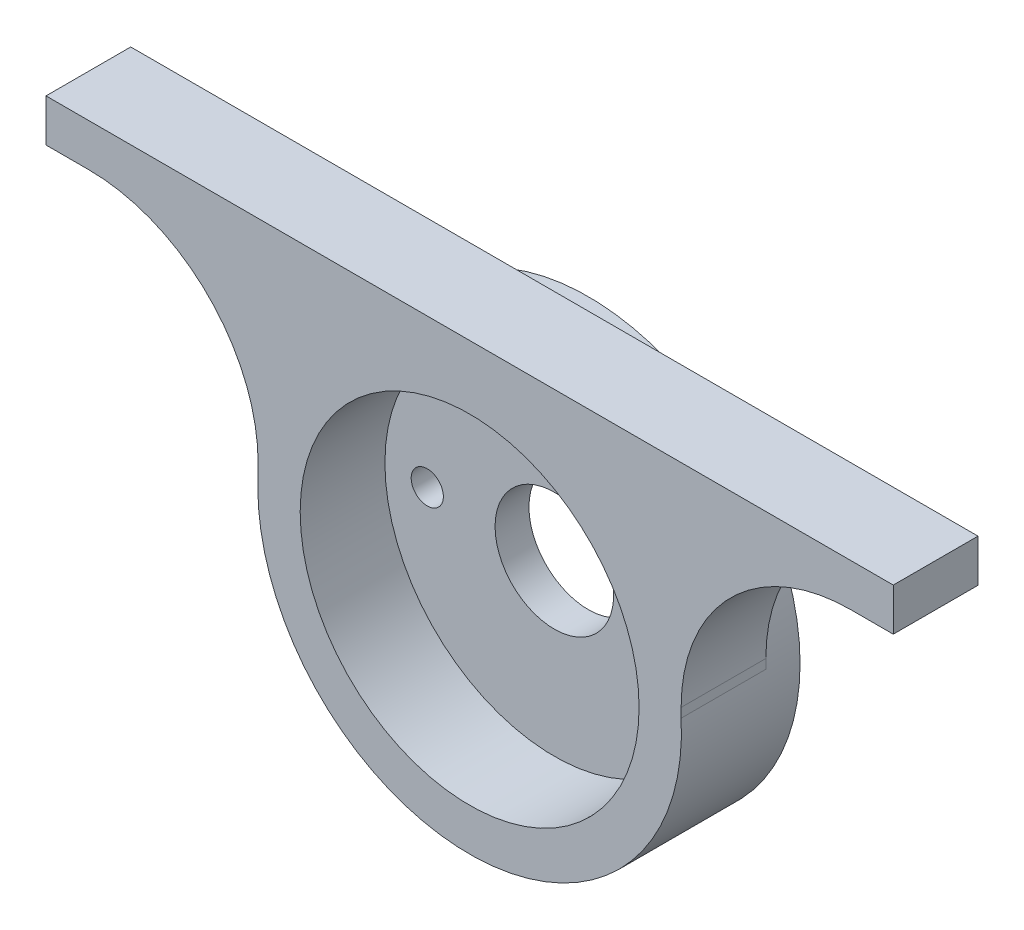
SolidWorks part; units mm, degrees
ref_plane "Front" through (0, 0, 0) normal (0, 0, 1) x (1, 0, 0)
ref_plane "Top" through (0, 0, 0) normal (0, 1, 0) x (1, 0, 0)
ref_plane "Right" through (0, 0, 0) normal (1, 0, 0) x (0, 0, -1)
sketch "Sketch1" plane through (0, 0, 0) normal (0, 0, 1) x (1, 0, 0)
  line L2 (-25, 11.2434) -> (-25, 13.7566)
  line L3 (-25, 13.7566) -> (25, 13.7566)
  line L4 (25, 11.2434) -> (25, 13.7566)
  line L5 (0, 12.5) -> (-25, 12.5) construction
  line L6 (0, 12.5) -> (25, 12.5) construction
  line L7 (25, 11.2434) -> (22.4809, 11.2434)
  line L8 (12.4809, 1.2434) -> (12.4809, 0.6908)
  line L9 (-12.4809, 0.6908) -> (-12.4809, 1.2434)
  line L10 (-22.4809, 11.2434) -> (-25, 11.2434)
  circle A0 centre (0, 0) radius 10
  arc A1 (-12.4809, 0.6908) -> (12.4809, 0.6908) centre (0, 0) ccw
  arc A4 (22.4809, 11.2434) -> (12.4809, 1.2434) centre (22.4809, 1.2434) ccw
  arc A5 (-12.4809, 1.2434) -> (-22.4809, 11.2434) centre (-22.4809, 1.2434) ccw
  point P4 (0, 12.5)
  point P12 (5.4623, 11.2434)
  dimension "D1" = 20
  dimension "D2" = 25
  dimension "D4" = 10
  dimension "D3" = 50
extrude "Boss-Extrude1" add sketch "Sketch1" along normal blind 5 contours L3 L4 A1 L2
sketch "Sketch3" plane through (0, 0, 0) normal (0, 0, -1) x (-1, 0, 0)
  line L0 (-7.5, 0) -> (7.5, 0) construction
  circle A0 centre (0, 0) radius 3.5
  circle A1 centre (0, 0) radius 12.5
  circle A2 centre (7.5, 0) radius 0.95
  circle A3 centre (-7.5, 0) radius 0.95
  dimension "D1" = 7
  dimension "D2" = 25
  dimension "D3" = 1.9
  dimension "D4" = 1.9
  dimension "D5" = 7.5
  dimension "D6" = 7.5
extrude "Boss-Extrude3" add sketch "Sketch3" along normal blind 2
sketch "Sketch4" plane through (0, 13.7566, 0) normal (0, 1, 0) x (1, 0, 0)
  line L0 (25, -5) -> (25, 0) construction
  line L1 (25, 0) -> (-25, 0) construction
  line L2 (-25, -5) -> (-25, 0) construction
  line L3 (25, -5) -> (-25, -5) construction
  circle A0 centre (-20, -5) radius 3
  circle A1 centre (20, -5) radius 3
  circle A2 centre (20, 0) radius 3
  circle A3 centre (-20, 0) radius 3
  dimension "D1" = 6
  dimension "D2" = 6
  dimension "D3" = 6
  dimension "D4" = 6
  dimension "D5" = 5
  dimension "D6" = 5
  dimension "D7" = 5
  dimension "D8" = 5
  dimension "D9" = 5
  dimension "D10" = 5
  dimension "D11" = 5
  dimension "D12" = 5
extrude "Cut-Extrude1" [suppressed] cut sketch "Sketch4" against normal through all
